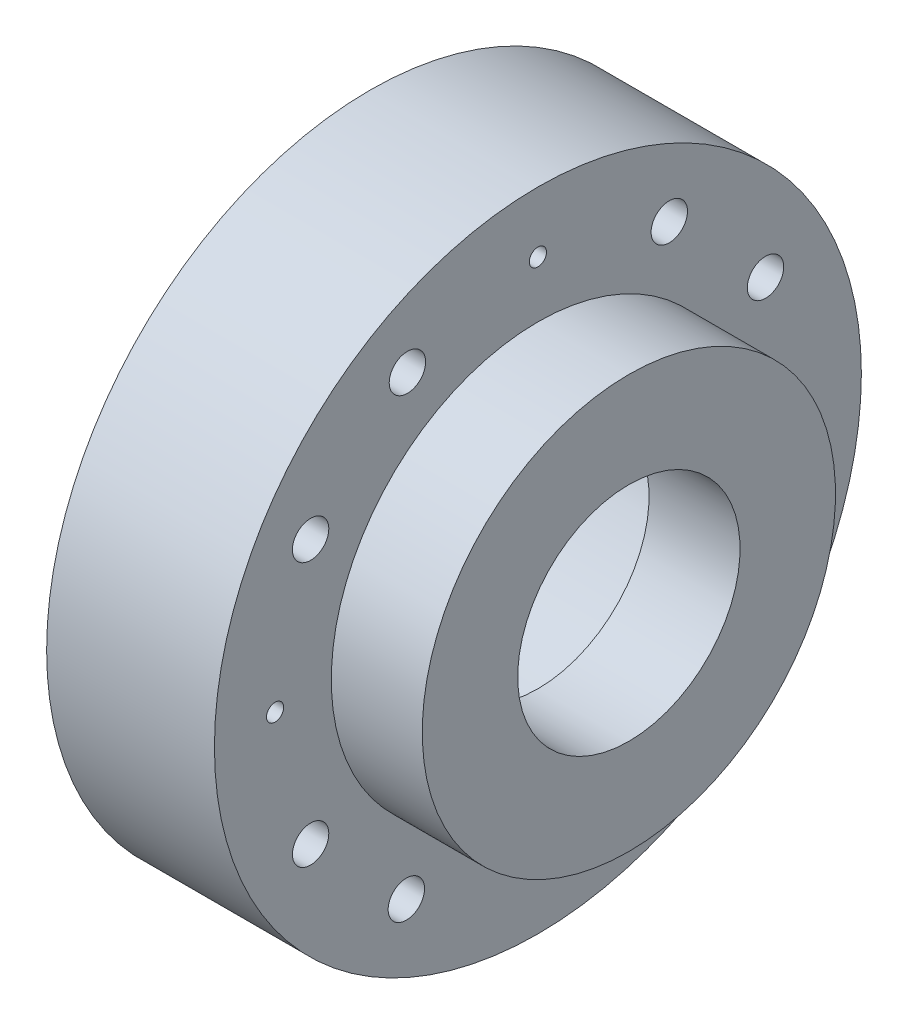
SolidWorks part; units mm, degrees
ref_plane "Plan de face" through (0, 0, 0) normal (0, 0, 1) x (1, 0, 0)
ref_plane "Plan de dessus" through (0, 0, 0) normal (0, 1, 0) x (1, 0, 0)
ref_plane "Plan de droite" through (0, 0, 0) normal (1, 0, 0) x (0, 0, -1)
sketch "Esquisse1" plane through (0, 0, 0) normal (0, 0, 1) x (1, 0, 0)
  line L0 (0, 0) -> (0, 102.2)
  line L1 (0, 102.2) -> (-45, 102.2)
  line L2 (-45, 102.2) -> (-45, 160)
  line L3 (-45, 160) -> (-128, 160)
  line L4 (-128, 160) -> (-128, 148.5)
  line L5 (-128, 148.5) -> (-111, 148.5)
  line L6 (-111, 148.5) -> (-111, 100)
  line L7 (-111, 100) -> (-58, 100)
  line L8 (-58, 100) -> (-58, 75)
  line L9 (-58, 75) -> (-45, 75)
  line L10 (-45, 75) -> (-45, 0)
  line L11 (-45, 0) -> (0, 0)
  point P13 (-45, 131.1)
  point P14 (-128, 154.25)
  point P15 (-22.5, 0)
  dimension "D1" = 160
  dimension "D2" = 148.5
  dimension "D3" = 100
  dimension "D4" = 75
  dimension "D5" = 83
  dimension "D6" = 45
  dimension "D7" = 13
  dimension "D8" = 53
  dimension "D9" = 17
  dimension "D10" = 102.2
revolve "Révolution1" add sketch "Esquisse1" angle 360 about L11
sketch "Esquisse2" plane through (-45, 0, 0) normal (-1, 0, 0) x (0, 0, 1)
  circle A0 centre (0, 0) radius 55
  dimension "D1" = 110
extrude "Enlèv. mat.-Extru.1" cut sketch "Esquisse2" against normal through all
sketch "Esquisse3" plane through (-111, 0, 0) normal (-1, 0, 0) x (0, 0, 1)
  line L0 (0, 0) -> (0, 130)
  line L1 (0, 0) -> (-130, 0)
  circle A0 centre (0, 0) radius 130
  circle A1 centre (-130, 0) radius 4.984
  circle A2 centre (0, 130) radius 4.984
  circle A3 centre (130, 0) radius 4.984
  circle A4 centre (0, -130) radius 4.984
  point P11 (0, 0)
  dimension "D1" = 260
  dimension "D2" = 9.968
  dimension "D3" = 9.968
hole_wizard "Trou taraudé M1010" positions "Esquisse3D2" profile "Esquisse11" tap size "M10" standard "ISO" end condition through all
sketch3d "Esquisse3D2"
  point P0 (-111, 0, -130)
  point P3 (-111, -130, 0)
  point P6 (-111, 0, 130)
  point P9 (-111, 130, 0)
sketch "Esquisse11" plane through (-111, 0, -130) normal (0, 1, 0) x (0, 0, 1)
  line L0 (0, 0) -> (0, 111)
  line L1 (0, 111) -> (4.25, 111)
  line L2 (4.25, 111) -> (4.25, 0)
  line L5 (4.25, 0) -> (0, 0)
  line L11 (0, -6.35) -> (0, 107.95) construction
  dimension "Diamètre du trou pour taraudage jusqu'au prochain" = 8.5
  dimension "Profondeur du trou pour taraudage jusqu'au prochain" = 111
cosmetic thread "Filetage de perçage2" parameters "D2"=10
cosmetic thread "Filetage de perçage3" parameters "D2"=10
cosmetic thread "Filetage de perçage4" parameters "D2"=10
cosmetic thread "Filetage de perçage5" parameters "D2"=10
hole_wizard "Perçage16" positions "Esquisse3D11" profile "Esquisse18" legacy
sketch3d "Esquisse3D11"
  line L0 (-111, 112.5833, -65) -> (-111, 0, 0)
  line L1 (-58, 0, 0) -> (-111, 0, 0) construction
  line L2 (-111, 0, 0) -> (-111, 130, 0) construction
  line L4 (-111, 65, -112.5833) -> (-111, 0, 0)
  line L6 (-111, 0, 0) -> (-111, 0, -130) construction
  line L7 (-111, 130, 0) -> (-111, 0, 0)
  circle A0 centre (-111, 0, 0) radius 130 construction
  point P0 (-111, 65, -112.5833)
  point P4 (-241, 0, 0)
  point P5 (-111, 112.5833, -65)
  dimension "D1" = 30
  dimension "D2" = 30
sketch "Esquisse18" plane through (-111, 65, -112.5833) normal (0, 1, 0) x (0, 0, 1)
  line L0 (0, 0) -> (0, 90)
  line L1 (0, 90) -> (9, 90)
  line L2 (9, 90) -> (9, 40)
  line L3 (9, 40) -> (12.5, 40)
  line L4 (12.5, 40) -> (12.5, 0)
  line L5 (12.5, 0) -> (0, 0)
  line L6 (0, 110) -> (0, -10) construction
  dimension "Diamètre" = 18
  dimension "Profondeur" = 90
  dimension "Diamètre chambrage" = 25
  dimension "Profondeur chambrage" = 40
hole_wizard "Perçage17" positions "Esquisse3D12" profile "Esquisse19" legacy
sketch3d "Esquisse3D12"
  line L0 (-111, 0, 130) -> (-111, 0, -0.6064)
  line L1 (-111, 0, -0.6064) -> (-111, -130, 0)
  line L3 (-111, -112.542, 65.0716) -> (-111, 0, -0.6064)
  line L5 (-111, -65.2624, 112.4314) -> (-111, 0, -0.6064)
  line L7 (-111, -112.6232, -64.9309) -> (-111, 0, -0.6064)
  line L9 (-111, -64.7372, -112.7346) -> (-111, 0, -0.6064)
  line L11 (-111, 65.2624, 112.4314) -> (-111, 0, -0.6064)
  line L13 (-111, 112.845, 64.5447) -> (-111, 0, -0.6064)
  line L15 (-111, 0, 0) -> (-111, 130, 0) construction
  line L16 (-111, 0, 0) -> (-111, 0, -130) construction
  circle A0 centre (-111, 0, 0) radius 130 construction
  point P0 (-111, 112.845, 64.5447)
  point P4 (-241, 0, 0)
  point P5 (-111, 65.2624, 112.4314)
  point P7 (-111, -65.2624, 112.4314)
  point P9 (-111, -112.542, 65.0716)
  point P11 (-111, -112.6232, -64.9309)
  point P13 (-111, -64.7372, -112.7346)
  point P41 (0, 0, 0)
  point P42 (0, 0, 0)
  dimension "D1" = 30
  dimension "D2" = 30
  dimension "D3" = 30
  dimension "D4" = 30
  dimension "D5" = 30
  dimension "D6" = 30
sketch "Esquisse19" plane through (-111, 112.845, 64.5447) normal (0, 1, 0) x (0, 0, 1)
  line L0 (0, 0) -> (0, 90)
  line L1 (0, 90) -> (9, 90)
  line L2 (9, 90) -> (9, 40)
  line L3 (9, 40) -> (12.5, 40)
  line L4 (12.5, 40) -> (12.5, 0)
  line L5 (12.5, 0) -> (0, 0)
  line L6 (0, 110) -> (0, -10) construction
  dimension "Diamètre" = 18
  dimension "Profondeur" = 90
  dimension "Diamètre chambrage" = 25
  dimension "Profondeur chambrage" = 40
